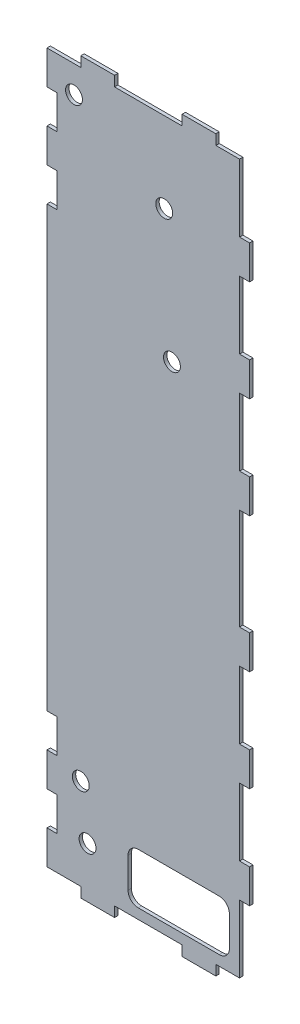
SolidWorks part; units mm, degrees
material "Acrylic (Medium-high impact)"
ref_plane "Front Plane" through (0, 0, 0) normal (0, 0, 1) x (1, 0, 0)
ref_plane "Top Plane" through (0, 0, 0) normal (0, 1, 0) x (1, 0, 0)
ref_plane "Right Plane" through (0, 0, 0) normal (1, 0, 0) x (0, 0, -1)
sketch "Sketch1" plane through (0, 0, 0) normal (0, 0, 1) x (1, 0, 0)
  line L0 (4, 43) -> (4, 173) construction
  line L1 (4, 173) -> (4, 205) construction
  line L2 (11.9974, 204.857) -> (5.7487, 30.1521) construction
  line L3 (14.254, 29.9877) -> (14.7131, 189.2432) construction
  line L4 (18.7468, 150.8315) -> (19.9997, 15.0738) construction
  line L5 (4, 15) -> (4, 43) construction
  line L6 (3.746, 15) -> (3.746, 43) construction
  line L7 (3.746, 43) -> (3.746, 173) construction
  line L8 (3.746, 173) -> (3.746, 205) construction
  line L9 (12.2513, 204.8479) -> (6.0026, 30.143) construction
  line L10 (14, 29.9885) -> (14.4591, 189.244) construction
  line L11 (19.0008, 150.8339) -> (20.2536, 15.0762) construction
  line L12 (0, 173) -> (0, 216) construction
  line L13 (0, 216) -> (60, 216) construction
  line L14 (60, 216) -> (60, 0) construction
  line L15 (60, 0) -> (0, 0) construction
  line L16 (0, 0) -> (0, 43) construction
  line L17 (3, 173) -> (3, 213) construction
  line L18 (3, 213) -> (57, 213) construction
  line L19 (57, 213) -> (57, 3) construction
  line L20 (57, 3) -> (3, 3) construction
  line L21 (3, 3) -> (3, 43) construction
  line L22 (0, 173) -> (3, 173) construction
  line L23 (0, 43) -> (3, 43) construction
  line L24 (0, 173) -> (0, 43)
  line L25 (0, 43) -> (3, 43)
  line L26 (3, 43) -> (3, 3)
  line L27 (3, 3) -> (57, 3)
  line L28 (57, 3) -> (57, 213)
  line L29 (57, 213) -> (3, 213)
  line L30 (3, 213) -> (3, 173)
  line L31 (3, 173) -> (0, 173)
  line L32 (4, 108) -> (57, 108) construction
  line L33 (57, 23) -> (60, 23)
  line L35 (57, 33) -> (60, 33)
  line L36 (60, 23) -> (60, 33)
  line L37 (57, 133) -> (60, 133)
  line L38 (57, 63) -> (60, 63)
  line L40 (57, 53) -> (60, 53)
  line L41 (60, 63) -> (60, 53)
  line L42 (57, 93) -> (60, 93)
  line L44 (57, 83) -> (60, 83)
  line L45 (60, 93) -> (60, 83)
  line L46 (3, 33) -> (0, 33)
  line L48 (3, 23) -> (0, 23)
  line L49 (0, 33) -> (0, 23)
  line L50 (3, 13) -> (0, 13)
  line L53 (0, 13) -> (0, 3)
  line L55 (10, 3) -> (10, 0)
  line L56 (10, 0) -> (20, 0)
  line L57 (20, 3) -> (20, 0)
  line L59 (40, 3) -> (40, 0)
  line L60 (40, 0) -> (50, 0)
  line L61 (50, 3) -> (50, 0)
  line L62 (60, 123) -> (60, 133)
  line L63 (57, 123) -> (60, 123)
  line L65 (57, 163) -> (60, 163)
  line L66 (60, 153) -> (60, 163)
  line L67 (57, 153) -> (60, 153)
  line L69 (57, 183) -> (60, 183)
  line L70 (60, 193) -> (60, 183)
  line L71 (57, 193) -> (60, 193)
  line L73 (40, 216) -> (50, 216)
  line L74 (50, 213) -> (50, 216)
  line L76 (40, 213) -> (40, 216)
  line L77 (10, 216) -> (20, 216)
  line L78 (20, 213) -> (20, 216)
  line L80 (10, 213) -> (10, 216)
  line L81 (3, 213) -> (0, 213)
  line L82 (0, 203) -> (0, 213)
  line L83 (3, 203) -> (0, 203)
  line L85 (3, 193) -> (0, 193)
  line L86 (0, 183) -> (0, 193)
  line L87 (3, 183) -> (0, 183)
  line L89 (27, 21) -> (51, 21)
  line L90 (24, 18) -> (24, 9)
  line L91 (27, 6) -> (51, 6)
  line L92 (54, 18) -> (54, 9)
  line L93 (0, 3) -> (3, 3)
  arc A0 (4, 205) -> (11.9974, 204.857) centre (8, 205) cw construction
  arc A1 (5.7487, 30.1521) -> (14.254, 29.9877) centre (10, 30) ccw construction
  arc A2 (14.7131, 189.2432) -> (35.9087, 169.2213) centre (34.713, 189.1856) cw construction
  arc A3 (35.9087, 169.2213) -> (18.7468, 150.8315) centre (37, 151) ccw construction
  arc A4 (19.9997, 15.0738) -> (4, 15) centre (12, 15) cw construction
  circle A5 centre (8, 205) radius 2.5
  circle A6 centre (34.713, 189.1856) radius 2.5
  circle A7 centre (10, 30) radius 2.5
  circle A8 centre (12, 15) radius 2.5
  arc A9 (3.746, 205) -> (12.2513, 204.8479) centre (8, 205) cw construction
  arc A10 (6.0026, 30.143) -> (14, 29.9885) centre (10, 30) ccw construction
  arc A11 (14.4591, 189.244) -> (35.9239, 168.9678) centre (34.713, 189.1856) cw construction
  arc A12 (35.9239, 168.9678) -> (19.0008, 150.8339) centre (37, 151) ccw construction
  arc A13 (20.2536, 15.0762) -> (3.746, 15) centre (12, 15) cw construction
  arc A14 (35.9087, 169.2213) -> (18.7468, 150.8315) centre (37, 151) ccw construction
  circle A15 centre (37, 151) radius 18 construction
  circle A16 centre (12, 15) radius 8 construction
  circle A17 centre (37, 109) radius 14 construction
  circle A18 centre (37, 151) radius 2.5
  circle A19 centre (37, 151) radius 16 construction
  circle A20 centre (37, 109) radius 5 construction
  circle A21 centre (37, 130) radius 16 construction
  circle A22 centre (37, 130) radius 5 construction
  circle A23 centre (37, 130) radius 2.5 construction
  arc A24 (27, 21) -> (24, 18) centre (27, 18) ccw
  arc A25 (54, 18) -> (51, 21) centre (51, 18) ccw
  arc A26 (51, 6) -> (54, 9) centre (51, 9) ccw
  arc A27 (24, 9) -> (27, 6) centre (27, 9) ccw
  point P42 (4, 108)
  point P45 (60, 108)
  point P120 (24, 21)
  point P127 (54, 21)
  point P132 (24, 6)
  dimension "D2" = 4
  dimension "D3" = 4
  dimension "D4" = 20
  dimension "D5" = 18
  dimension "D7" = 8
  dimension "D8" = 832
  dimension "D9" = 5
  dimension "D22" = 28
  dimension "D23" = 37
  dimension "D24" = 10
  dimension "D25" = 32
  dimension "D26" = 32
  dimension "D27" = 10
  dimension "D21" = 10
  dimension "D37" = 3
  dimension "D38" = 3
  dimension "D39" = 3
  dimension "D40" = 3
  dimension "D1" = 130
  dimension "D6" = 28
  dimension "D11" = 13
  dimension "D12" = 43
  dimension "D13" = 32
  dimension "D14" = 60
  dimension "D15" = 12
  dimension "D16" = 10
  dimension "D17" = 216
  dimension "D18" = 10
  dimension "D19" = 22
  dimension "D29" = 20
  dimension "D28" = 20
  dimension "D30" = 20
  dimension "D31" = 7
  dimension "D32" = 20
  dimension "D33" = 3
  dimension "D34" = 3
  dimension "D35" = 30
  dimension "D36" = 15
  dimension "D10" = 0.254
  dimension "D20" = 3
extrude "Boss-Extrude2" add sketch "Sketch1" along normal blind 1 contours L46 L49 L48 L26 | L30 L31 L24 L25 L26 L27 L28 L29 A23 A18 A8 A7 A6 A5 | L57 L27 L55 L56 | L61 L27 L59 L60 | L33 L36 L35 L28 | L41 L38 L28 L40 | L28 L63 L62 L37 | L28 L67 L66 L65 | L71 L28 L69 L70 | L76 L29 L74 L73 | L80 L29 L78 L77 | L83 L30 L81 L82 | L87 L30 L85 L86 | L53 L93 L26 L50 | L45 L42 L28 L44
